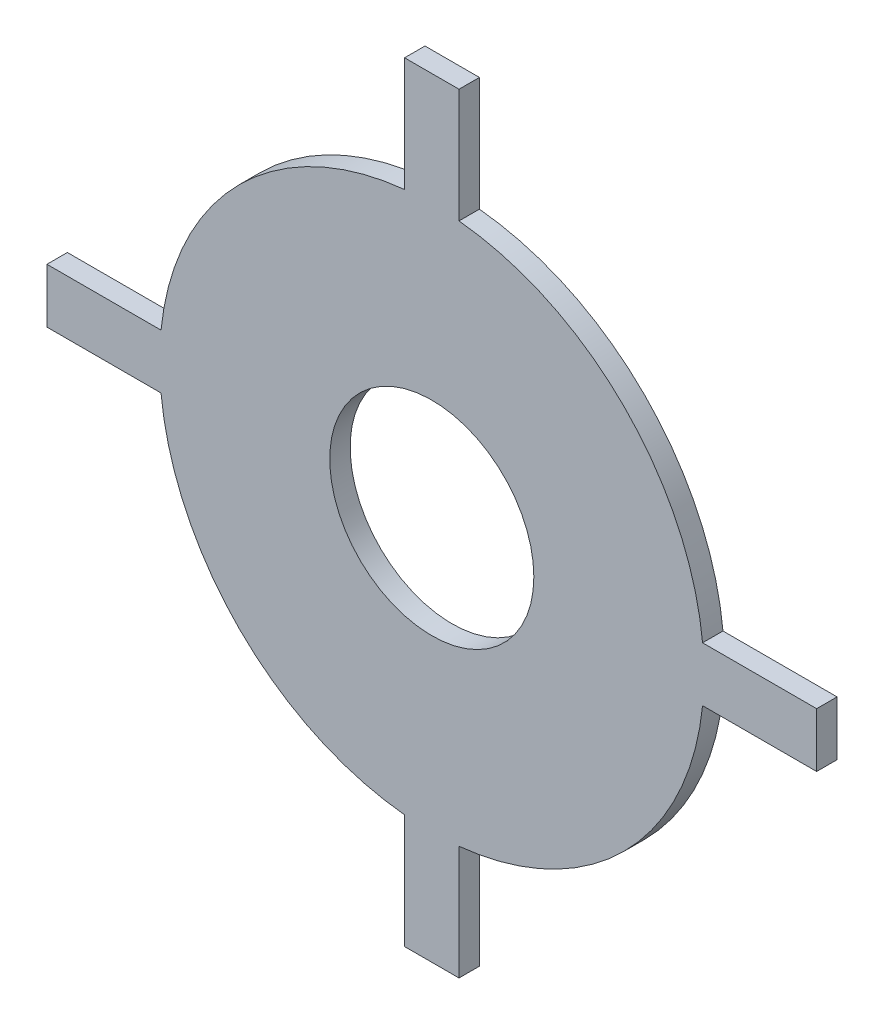
SolidWorks part; units mm, degrees
ref_plane "前视基准面" through (0, 0, 0) normal (0, 0, 1) x (1, 0, 0)
ref_plane "上视基准面" through (0, 0, 0) normal (0, 1, 0) x (1, 0, 0)
ref_plane "右视基准面" through (0, 0, 0) normal (1, 0, 0) x (0, 0, -1)
other "Configuration Table"
sketch "草图1" plane through (0, 0, 0) normal (0, 0, 1) x (1, 0, 0)
  circle A0 centre (0, 0) radius 20
  circle A1 centre (0, 0) radius 7.5
extrude "凸台-拉伸1" add sketch "草图1" along normal blind 1.5
sketch "草图2" plane through (0, 0, 0) normal (0, 0, 1) x (1, 0, 0)
  line L1 (19, -2) -> (28.2843, -2)
  line L2 (19, -2) -> (19, 2)
  line L3 (19, 2) -> (28.2843, 2)
  line L4 (28.2843, -2) -> (28.2843, 2)
  line L6 (2, 19) -> (-2, 19)
  line L7 (2, 19) -> (2, 28.2843)
  line L8 (2, 28.2843) -> (-2, 28.2843)
  line L9 (-2, 19) -> (-2, 28.2843)
  line L11 (-19, 2) -> (-28.2843, 2)
  line L12 (-19, 2) -> (-19, -2)
  line L13 (-19, -2) -> (-28.2843, -2)
  line L14 (-28.2843, 2) -> (-28.2843, -2)
  line L16 (-2, -19) -> (2, -19)
  line L17 (-2, -19) -> (-2, -28.2843)
  line L18 (-2, -28.2843) -> (2, -28.2843)
  line L19 (2, -19) -> (2, -28.2843)
extrude "凸台-拉伸2" add sketch "草图2" along normal blind 1.5
